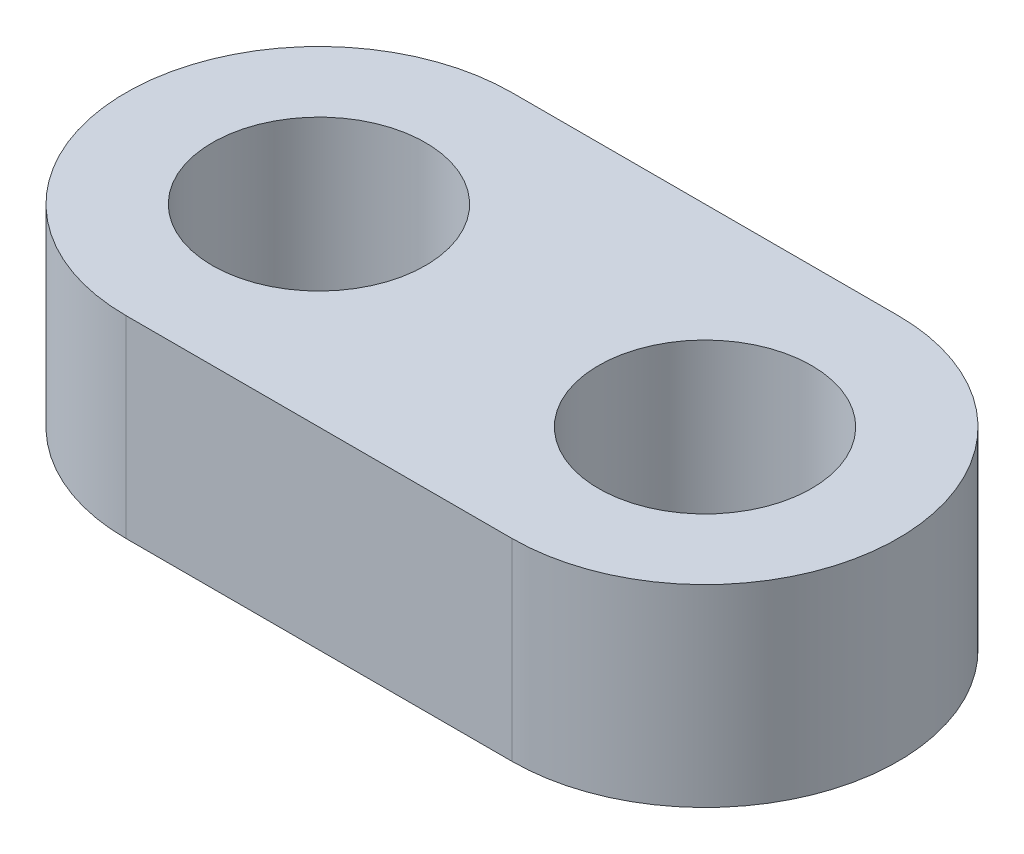
SolidWorks part; units mm, degrees
ref_plane "Front Plane" through (0, 0, 0) normal (0, 0, 1) x (1, 0, 0)
ref_plane "Top Plane" through (0, 0, 0) normal (0, 1, 0) x (1, 0, 0)
ref_plane "Right Plane" through (0, 0, 0) normal (1, 0, 0) x (0, 0, -1)
sketch "Sketch1" plane through (0, 0, 0) normal (0, 1, 0) x (1, 0, 0)
  line L0 (-3.175, 0) -> (3.175, 0) construction
  line L1 (-3.175, 3.175) -> (3.175, 3.175)
  line L2 (-3.175, -3.175) -> (3.175, -3.175)
  line L3 (0, 3.175) -> (0, -3.175) construction
  arc A0 (-3.175, 3.175) -> (-3.175, -3.175) centre (-3.175, 0) ccw
  arc A1 (3.175, -3.175) -> (3.175, 3.175) centre (3.175, 0) ccw
  circle A2 centre (-3.175, 0) radius 1.7526
  circle A3 centre (3.175, 0) radius 1.7526
  point P2 (0, 0)
  dimension "D2" = 3.175
  dimension "D3" = 3.5052
  dimension "D1" = 6.35
extrude "Boss-Extrude1" add sketch "Sketch1" along normal blind 3.175
